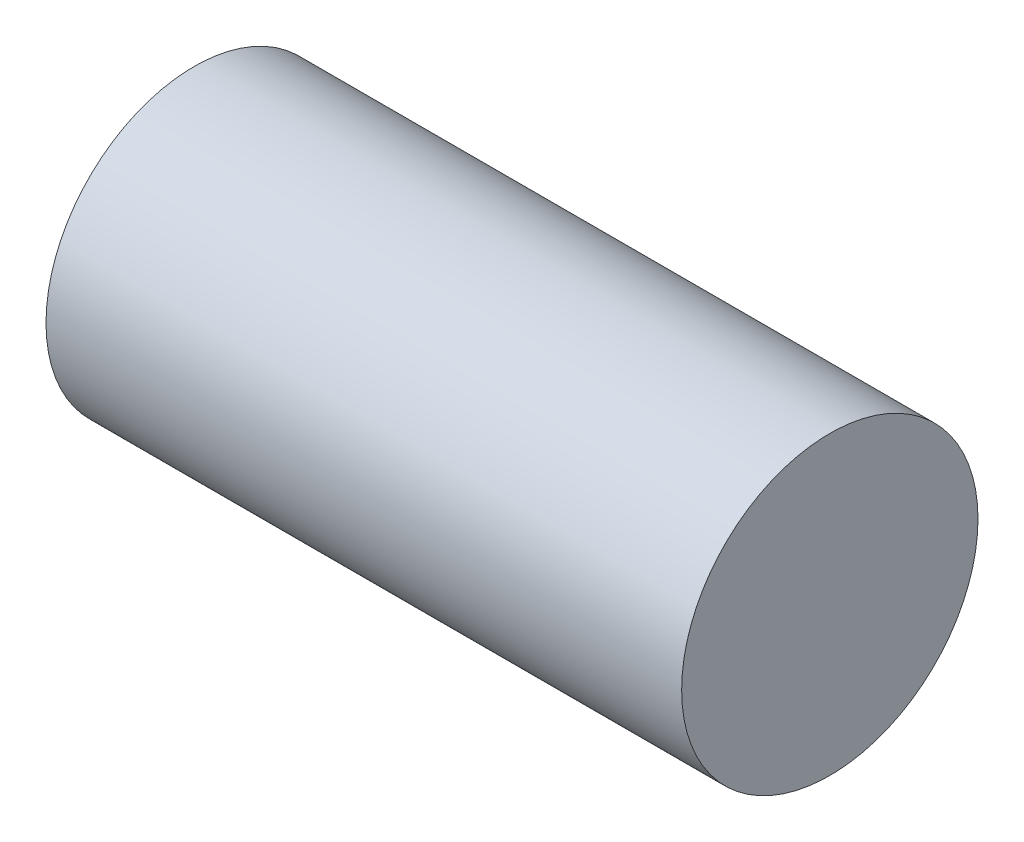
SolidWorks part; units mm, degrees
ref_plane "Front Plane" through (0, 0, 0) normal (0, 0, 1) x (1, 0, 0)
ref_plane "Top Plane" through (0, 0, 0) normal (0, 1, 0) x (1, 0, 0)
ref_plane "Right Plane" through (0, 0, 0) normal (1, 0, 0) x (0, 0, -1)
sketch "CurveSketch" plane through (0, 0, 0) normal (1, 0, 0) x (0, 0, -1)
  circle A0 centre (4.971, -9.313) radius 7.919
  dimension "D1" = 15.838
extrude "CurveBoss" add sketch "CurveSketch" along normal mid plane 33.971
